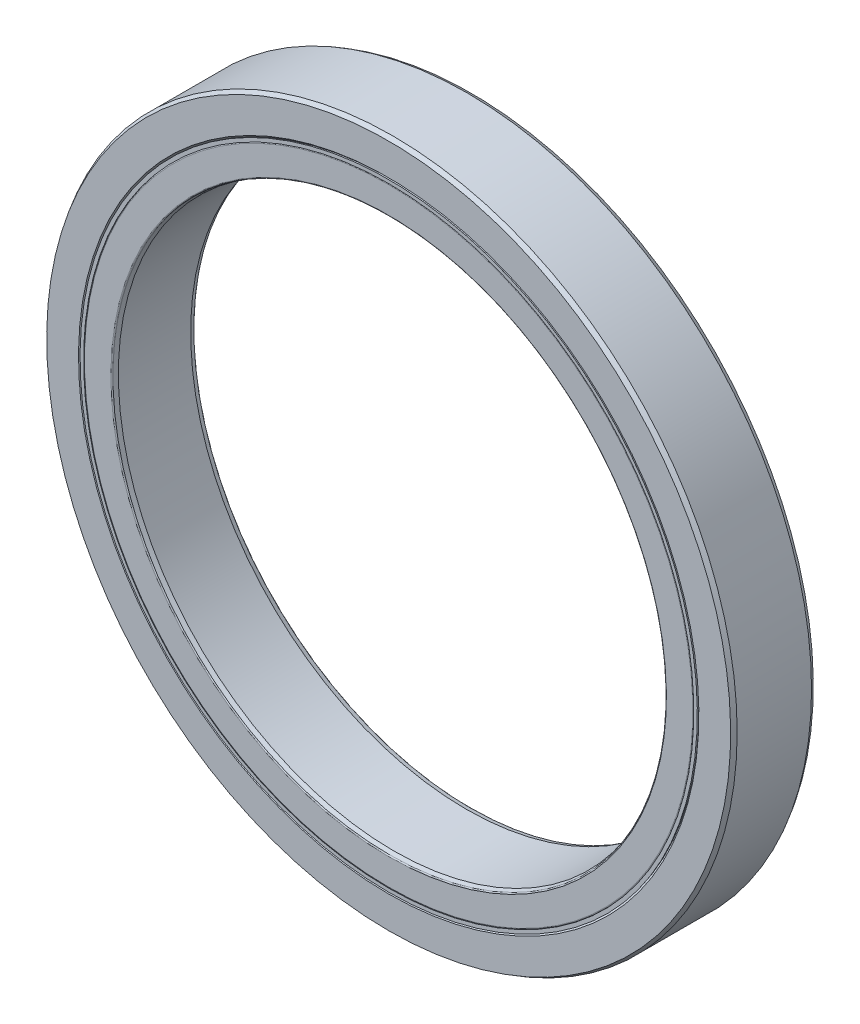
SolidWorks part; units mm, degrees
ref_plane "Front Plane" through (0, 0, 0) normal (0, 0, 1) x (1, 0, 0)
ref_plane "Top Plane" through (0, 0, 0) normal (0, 1, 0) x (1, 0, 0)
ref_plane "Right Plane" through (0, 0, 0) normal (1, 0, 0) x (0, 0, -1)
sketch "Sketch1" plane through (0, 0, 0) normal (0, 0, 1) x (1, 0, 0)
  line L0 (-25, 0) -> (25, 0) construction
  line L1 (-20, 0) -> (20, 0) construction
  circle A0 centre (0, 0) radius 20 construction
  circle A1 centre (0, 0) radius 25 construction
  point P3 (0, 0)
  point P6 (0, 0)
  point P7 (0, -20)
  point P11 (0, -25)
  point P12 (0, 20)
  point P13 (0, 25)
  dimension "OD" = 50
  dimension "ID" = 40
sketch "Sketch2" plane through (0, 0, 0) normal (1, 0, 0) x (0, 0, -1)
  line L0 (-3, 25) -> (3, 25) construction
  line L1 (0, 25) -> (0, -25) construction
  line L2 (2.7, 25) -> (-2.7, 25)
  line L3 (-2.7, 25) -> (-3, 24.8268)
  line L4 (-3, 24.8268) -> (-3, 22.5185)
  line L5 (-2.5245, 22.25) -> (-1.8745, 22.25)
  line L6 (2.5245, 22.25) -> (1.8745, 22.25)
  line L7 (3, 24.8268) -> (3, 22.5185)
  line L8 (2.7, 25) -> (3, 24.8268)
  line L9 (-1.8745, 22.25) -> (-1.8745, 23.1667) construction
  line L10 (-1.8745, 23.1667) -> (-1.8745, 24.0833) construction
  line L11 (0, 25) -> (0, -25) construction
  line L12 (-3, 0) -> (3, 0) construction
  line L13 (3, 20) -> (-3, 20) construction
  line L14 (-3, 20) -> (-3, -20) construction
  line L15 (-3, -20) -> (3, -20) construction
  line L16 (3, 25) -> (3, -25) construction
  line L17 (-1.8745, 24.0833) -> (-1.8745, 25) construction
  line L18 (-1.8745, 24.0833) -> (0, 24.0833) construction
  line L20 (-2.5245, 22.25) -> (-2.85, 22.3685)
  line L21 (-2.85, 22.3685) -> (-3, 22.5185)
  line L26 (2.85, 22.3685) -> (3, 22.5185)
  line L27 (2.5245, 22.25) -> (2.85, 22.3685)
  arc A0 (-1.8745, 22.25) -> (1.8745, 22.25) centre (0, 22.2083) cw
  circle A1 centre (0, 22.2083) radius 1.875 construction
  point P17 (0, 0)
  point P21 (0, 25)
  point P30 (0, -20)
  dimension "Approx. Ball Dia." = 3.75
  dimension "Width" = 6
  dimension "For Shaft Diameter" = 40
  dimension "For Housing ID" = 50
  dimension "D4" = 44.5
  dimension "D2" = 20
  dimension "D5" = 45
  dimension "D1" = 30
  dimension "D6" = 0.3
  dimension "D7" = 0.15
sketch "Sketch3" plane through (0, 0, 0) normal (1, 0, 0) x (0, 0, -1)
  line L14 (-2.5245, 22.25) -> (-2.85, 22.3685) construction
  line L15 (-2.85, 22.3685) -> (-3, 22.5185) construction
  line L16 (-3, 24.8268) -> (-3, 22.5185) construction
  line L17 (-2.7, 25) -> (-3, 24.8268) construction
  line L18 (2.7, 25) -> (-2.7, 25) construction
  line L19 (2.7, 25) -> (3, 24.8268) construction
  line L20 (3, 24.8268) -> (3, 22.5185) construction
  line L21 (2.85, 22.3685) -> (3, 22.5185) construction
  line L22 (2.5245, 22.25) -> (2.85, 22.3685) construction
  line L23 (2.5245, 22.25) -> (1.8745, 22.25) construction
  line L24 (-2.5245, 22.25) -> (-1.8745, 22.25) construction
  line L25 (-2.5245, 22.25) -> (-2.85, 22.3685)
  line L26 (-2.85, 22.3685) -> (-3, 22.5185)
  line L27 (-3, 24.8268) -> (-3, 22.5185)
  line L28 (-2.7, 25) -> (-3, 24.8268)
  line L29 (2.7, 25) -> (-2.7, 25)
  line L30 (2.7, 25) -> (3, 24.8268)
  line L31 (3, 24.8268) -> (3, 22.5185)
  line L32 (2.85, 22.3685) -> (3, 22.5185)
  line L33 (2.5245, 22.25) -> (2.85, 22.3685)
  line L34 (2.5245, 22.25) -> (1.8745, 22.25)
  line L35 (-2.5245, 22.25) -> (-1.8745, 22.25)
  arc A2 (1.8745, 22.25) -> (-1.8745, 22.25) centre (0, 22.2083) ccw construction
  arc A3 (1.8745, 22.25) -> (-1.8745, 22.25) centre (0, 22.2083) ccw
revolve "Revolve1" add sketch "Sketch3" angle 360 about L12
sketch "Sketch4" plane through (0, 0, 0) normal (1, 0, 0) x (0, 0, -1)
  line L0 (0, 25) -> (0, -25) construction
  line L1 (0, 25) -> (0, -25) construction
  line L2 (-2.6251, 20) -> (-2.9361, 20.0833)
  line L3 (-3, 20.1667) -> (-3, 22.0804)
  line L4 (3, -24.8268) -> (3, 24.8268) construction
  line L5 (-2.9137, 22.1667) -> (-1.8745, 22.1667)
  line L6 (-2.6251, 20) -> (2.6251, 20)
  line L7 (3, 24.8268) -> (3, 22.5185) construction
  line L8 (2.6251, 20) -> (2.9361, 20.0833)
  line L9 (0, 24.0833) -> (0, 20) construction
  line L10 (3, 20.1667) -> (3, 22.0804)
  line L11 (2.9137, 22.1667) -> (1.8745, 22.1667)
  line L12 (2.6251, 20) -> (2.6251, 20.0833) construction
  line L13 (2.6251, 20.0833) -> (2.6251, 20.1667) construction
  line L14 (2.6251, 20.1667) -> (2.6251, 20.25) construction
  line L15 (2.6251, 20.25) -> (2.6251, 20.3333) construction
  circle A0 centre (0, 22.2083) radius 1.875 construction
  arc A1 (1.8745, 22.1667) -> (-1.8745, 22.1667) centre (0, 22.2083) cw
  arc A2 (3, 22.0804) -> (2.9137, 22.1667) centre (2.9137, 22.0804) ccw
  arc A3 (-3, 22.0804) -> (-2.9137, 22.1667) centre (-2.9137, 22.0804) cw
  arc A4 (2.9361, 20.0833) -> (3, 20.1667) centre (2.9137, 20.1667) ccw
  arc A5 (-2.9361, 20.0833) -> (-3, 20.1667) centre (-2.9137, 20.1667) cw
  point P14 (3, 20.1005)
  point P36 (0, 20.3333)
  dimension "D1" = 15
revolve "Revolve2" add sketch "Sketch4" angle 360 about L12
sketch "Sketch5" plane through (0, 0, 0) normal (1, 0, 0) x (0, 0, -1)
  line L0 (-1.875, 22.2083) -> (1.875, 22.2083)
  arc A2 (-1.875, 22.2083) -> (1.875, 22.2083) centre (0, 22.2083) cw
  arc A3 (1.8745, 22.25) -> (-1.8745, 22.25) centre (0, 22.2083) ccw construction
revolve "Revolve3" add sketch "Sketch5" angle 360 about L0
pattern_circular "CirPattern1" count 24 over 360 about axis through (0, 0, 0) along (0, 0, 1) of bodies 104
sketch "Sketch6" plane through (0, 0, 0) normal (1, 0, 0) x (0, 0, -1)
  line L1 (-2.8268, 22.25) -> (-1.875, 22.25)
  line L2 (-3, 22.15) -> (-3, 22.4067)
  line L3 (-2.96, 22.3667) -> (-1.875, 22.3667)
  line L4 (-1.875, 22.25) -> (-1.875, 22.3667)
  line L5 (-3, 20.1667) -> (-3, 22.0804) construction
  line L6 (-2.7, 25) -> (-3, 24.8268) construction
  line L7 (0, 25) -> (0, 20) construction
  line L8 (2.96, 22.3667) -> (1.875, 22.3667)
  line L9 (1.875, 22.25) -> (1.875, 22.3667)
  line L10 (2.8268, 22.25) -> (1.875, 22.25)
  line L11 (3, 22.15) -> (3, 22.4067)
  line L13 (-2.9137, 22.1667) -> (-1.8745, 22.1667) construction
  line L14 (-3, 22.15) -> (-2.8268, 22.25)
  line L15 (-2.5245, 22.25) -> (-1.8745, 22.25) construction
  line L16 (3, 22.15) -> (2.8268, 22.25)
  arc A0 (-3, 22.4067) -> (-2.96, 22.3667) centre (-2.96, 22.4067) ccw
  circle A1 centre (0, 22.2083) radius 1.875 construction
  arc A2 (3, 22.4067) -> (2.96, 22.3667) centre (2.96, 22.4067) cw
  point P26 (-3, 22.3667)
  dimension "D3" = 0.04
  dimension "D1" = 0.2
  dimension "D2" = 0.1
revolve "Revolve4" add sketch "Sketch6" angle 360 about L12
sketch "Sketch7" plane through (0, 0, 0) normal (1, 0, 0) x (0, 0, -1)
  line L3 (-1.875, 22.3667) -> (-2.8544, 22.3667)
  line L4 (-2.96, 22.3667) -> (-1.875, 22.3667) construction
  line L7 (0, 20.3333) -> (0, 20) construction
  line L8 (0, 25) -> (0, -25) construction
  line L21 (-2.8544, 22.3667) -> (-2.9036, 22.358)
  line L22 (-2.9, 22.3167) -> (-2.925, 22.3167)
  line L23 (-2.925, 22.1667) -> (-1.875, 22.1667)
  line L24 (-1.875, 22.1667) -> (-1.875, 22.3667)
  line L25 (-2.9137, 22.1667) -> (-1.8745, 22.1667) construction
  line L26 (-3, 22.4067) -> (-3, 22.1667) construction
  line L27 (-3, 22.1667) -> (-2.925, 22.1667) construction
  line L28 (-2.8544, 22.3667) -> (-2.8544, 22.3167) construction
  line L29 (-2.8544, 22.3167) -> (-2.8544, 22.2667) construction
  line L30 (-2.8544, 22.2667) -> (-2.8544, 22.2167) construction
  line L31 (-2.8544, 22.2167) -> (-2.8544, 22.1667) construction
  circle A2 centre (0, 22.2083) radius 1.875 construction
  arc A9 (-2.9036, 22.358) -> (-2.9, 22.3167) centre (-2.9, 22.3375) ccw
  arc A10 (-2.925, 22.3167) -> (-2.925, 22.1667) centre (-2.925, 22.2417) ccw
  dimension "D1" = 0.025
  dimension "D2" = 10
revolve "Revolve5" add sketch "Sketch7" angle 360 about L12
equation "\"D4@Sketch2\"=\"OD@Sketch1\"*.89"
equation "\"D1@Sketch6\"=(\"OD@Sketch1\"-\"ID@Sketch1\")*.02"
equation "\"D2@Sketch6\"=\"D1@Sketch6\"*.5"
equation "\"D3@Sketch6\"=\"D1@Sketch6\"*.2"
equation "\"D6@Sketch2\"=\"Width@Sketch2\"*.05"
equation "\"D7@Sketch2\"=\"D6@Sketch2\"*.5"
equation "\"D1@CirPattern1\" =  ( pi * \"OD@Sketch1\" )  * .5625 / \"Approx. Ball Dia.@Sketch2\""
equation "\"Approx. Ball Dia.@Sketch2\"=(\"OD@Sketch1\"-\"ID@Sketch1\")*.5*.75"
